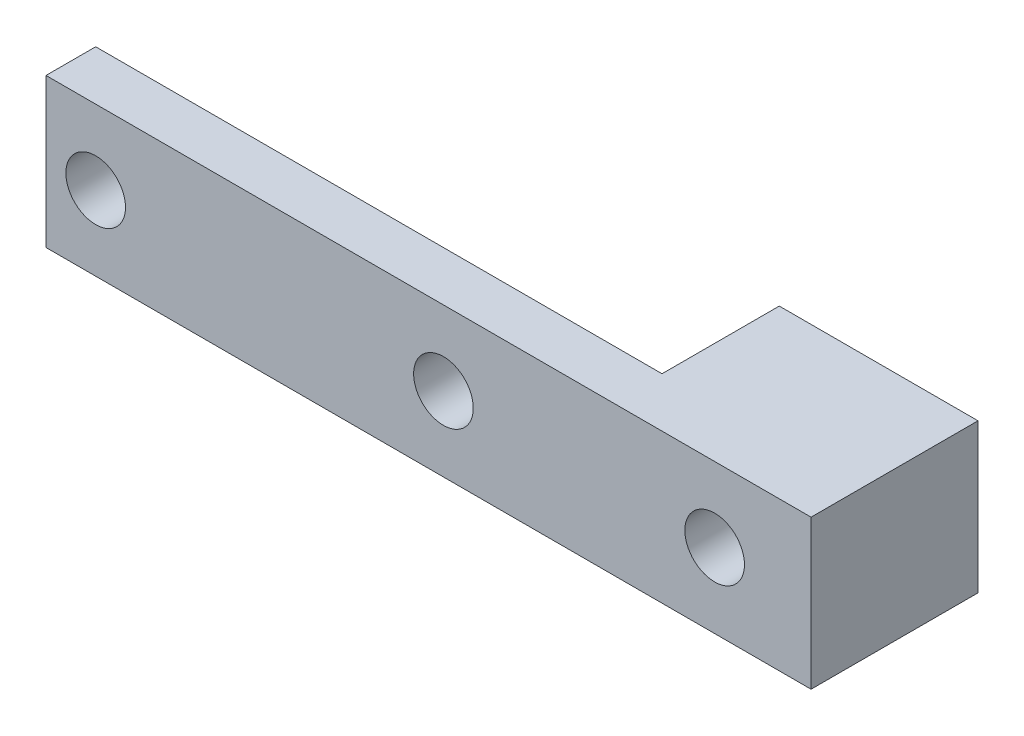
SolidWorks part; units mm, degrees
ref_plane "Front Plane" through (0, 0, 0) normal (1, 0, 0) x (0, 1, 0)
ref_plane "Top Plane" through (0, 0, 0) normal (0, 0, 1) x (0, 1, 0)
ref_plane "Right Plane" through (0, 0, 0) normal (0, 1, 0) x (-1, 0, 0)
sketch "Sketch1" plane through (0, 0, 0) normal (0, 0, 1) x (0, 1, 0)
  line L0 (0, 19.25) -> (0, -19.25) construction
  line L1 (-3.75, -19.25) -> (3.75, -19.25)
  line L2 (-3.75, -19.25) -> (-3.75, 19.25)
  line L3 (-3.75, 19.25) -> (3.75, 19.25)
  line L4 (3.75, -19.25) -> (3.75, 19.25)
  circle A0 centre (0, 16.75) radius 1.5
  circle A1 centre (0, -0.75) radius 1.5
  circle A2 centre (0, -14.398) radius 1.5
  point P0 (0, 0)
  dimension "D3" = 3
  dimension "D4" = 3
  dimension "D6" = 3
  dimension "D1" = 38.5
  dimension "D2" = 7.5
  dimension "D5" = 17.5
  dimension "D7" = 2.5
  dimension "D8" = 13.648
extrude "Boss-Extrude1" add sketch "Sketch1" along normal blind 2.5 contours L0 L3 L2 L1 A2 A1 A0 | L3 L0 A0 A1 A2 L1 L4
sketch "Sketch2" plane through (0, 0, 0) normal (0, 0, -1) x (1, 0, 0)
  line L0 (9.25, 3.75) -> (9.25, -3.75)
  line L1 (19.25, 3.75) -> (-19.25, 3.75) construction
  line L2 (19.25, -3.75) -> (-19.25, -3.75) construction
  line L3 (19.25, 3.75) -> (19.25, -3.75) construction
  line L4 (9.25, 3.75) -> (19.25, 3.75)
  line L5 (19.25, 3.75) -> (19.25, -3.75)
  line L6 (19.25, -3.75) -> (9.25, -3.75)
  circle A0 centre (14.398, 0) radius 1.5
  dimension "D1" = 10
extrude "Boss-Extrude2" add sketch "Sketch2" along normal blind 5.9
